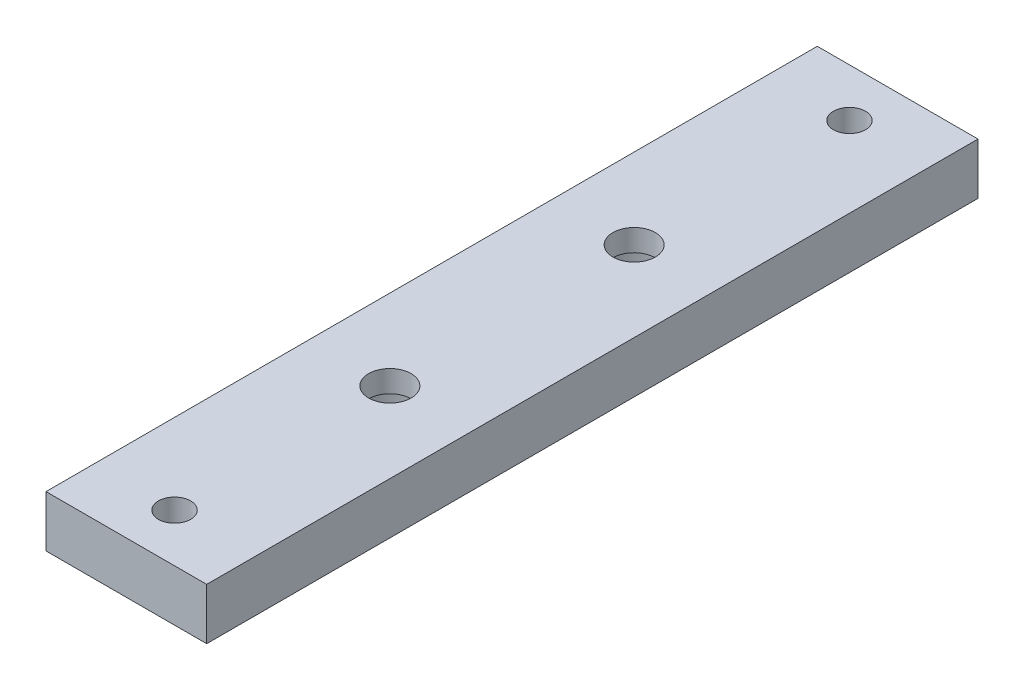
SolidWorks part; units mm, degrees
ref_plane "Přední rovina" through (0, 0, 0) normal (0, 0, 1) x (1, 0, 0)
ref_plane "Horní rovina" through (0, 0, 0) normal (0, 1, 0) x (1, 0, 0)
ref_plane "Pravá rovina" through (0, 0, 0) normal (1, 0, 0) x (0, 0, -1)
sketch "Skica1" plane through (0, 0, 0) normal (0, 1, 0) x (1, 0, 0)
  line L1 (-12.5, 60) -> (12.5, 60)
  line L2 (-12.5, 60) -> (-12.5, -60)
  line L3 (-12.5, -60) -> (12.5, -60)
  line L4 (12.5, 60) -> (12.5, -60)
  line L5 (-12.5, 60) -> (12.5, -60) construction
  line L6 (-12.5, -60) -> (12.5, 60) construction
  point P0 (0, 0)
  dimension "D1" = 25
  dimension "D2" = 120
extrude "Přidat vysunutím1" add sketch "Skica1" along normal blind 8
sketch "Skica2" plane through (0, 8, 0) normal (0, 1, 0) x (1, 0, 0)
  line L0 (0, -60) -> (0, 60)
  line L1 (-12.5, -60) -> (12.5, -60) construction
  line L2 (12.5, 60) -> (-12.5, 60) construction
  point P6 (0, 52.5)
  point P7 (0, -52.5)
  point P8 (0, 0)
  dimension "D1" = 52.5
  dimension "D2" = 52.5
hole_wizard "Díry pro kolík, velikost mm2" positions "Skica3" profile "Skica4" hole size "Ø4.0" standard "ANSI Metric"
sketch "Skica3" plane through (0, 8, 0) normal (0, 1, 0) x (1, 0, 0)
  point P0 (0, -52.5)
  point P3 (0, 52.5)
sketch "Skica4" plane through (0, 8, 52.5) normal (1, 0, 0) x (0, 0, 1)
  line L0 (0, 0) -> (0, 6)
  line L1 (0, 6) -> (2.5, 6)
  line L2 (2.5, 6) -> (2.5, 0)
  line L5 (2.5, 0) -> (0, 0)
  line L10 (0, 6) -> (-2.5, 6) construction
  line L11 (0, -6.35) -> (0, 107.95) construction
  dimension "Průměr díry" = 5
  dimension "Hloubka díry" = 6
  dimension "Úhel vrtání" = 180
sketch "Skica7" plane through (0, 0, 0) normal (0, -1, 0) x (1, 0, 0)
  line L0 (0, -60) -> (0, 60)
  point P2 (0, 52.5)
  point P3 (0, -52.5)
hole_wizard "Díry pro kolík, velikost mm2" positions "Skica8" profile "Skica9" hole size "Ø4.0" standard "ANSI Metric"
sketch "Skica8" plane through (0, 0, 0) normal (0, -1, 0) x (-1, 0, 0)
  point P0 (0, -52.5)
  point P3 (0, 52.5)
sketch "Skica9" plane through (0, 0, 52.5) normal (1, 0, 0) x (0, 0, -1)
  line L0 (0, 0) -> (0, 1.7)
  line L1 (0, 1.7) -> (2, 1.7)
  line L2 (2, 1.7) -> (2, 0)
  line L5 (2, 0) -> (0, 0)
  line L10 (0, 1.7) -> (-2, 1.7) construction
  line L11 (0, -6.35) -> (0, 107.95) construction
  dimension "Průměr díry" = 4
  dimension "Hloubka díry" = 1.7
  dimension "Úhel vrtání" = 180
sketch "Skica10" plane through (0, 0, 0) normal (0, -1, 0) x (1, 0, 0)
  line L0 (0, 60) -> (0, -60)
  line L1 (12.5, -60) -> (-12.5, -60) construction
  point P5 (0, 19)
  point P6 (0, -19)
  dimension "D1" = 19
  dimension "D2" = 19
hole_wizard "Válcové zahloubení pro M6 šrouby s válcovou hlavou zaoblenou1" positions "Skica11" profile "Skica12" counterbore size "M6" standard "ANSI Metric" end condition through all
sketch "Skica11" plane through (0, 0, 0) normal (0, -1, 0) x (-1, 0, 0)
  point P0 (0, -19)
  point P3 (0, 19)
sketch "Skica12" plane through (0, 0, 19) normal (1, 0, 0) x (0, 0, -1)
  line L0 (0, 0) -> (0, 8)
  line L1 (0, 8) -> (3.3, 8)
  line L3 (3.3, 8) -> (3.3, 4.6)
  line L4 (3.3, 4.6) -> (7, 4.6)
  line L5 (7, 4.6) -> (7, 0)
  line L7 (7, 0) -> (0, 0)
  line L11 (0, -6.35) -> (0, 107.95) construction
  dimension "Průměr díry skrz" = 6.6
  dimension "Hloubka díry skrz" = 8
  dimension "Průměr válcového zahloubení" = 14
  dimension "Hloubka válcového zahloubení" = 4.6
